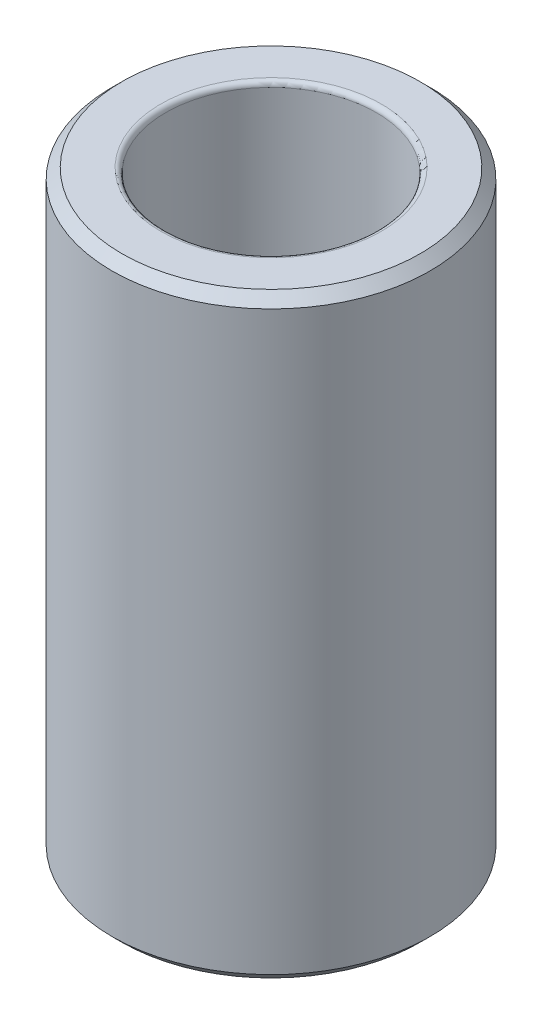
SolidWorks part; units mm, degrees
material "Stainless Steel (ferritic)"
ref_plane "Front Plane" through (0, 0, 0) normal (0, 0, 1) x (1, 0, 0)
ref_plane "Top Plane" through (0, 0, 0) normal (0, 1, 0) x (1, 0, 0)
ref_plane "Right Plane" through (0, 0, 0) normal (1, 0, 0) x (0, 0, -1)
sketch "Sketch2" plane through (0, 0, 0) normal (0, 1, 0) x (1, 0, 0)
  circle A0 centre (0, 0) radius 4
  circle A1 centre (0, 0) radius 2.65
  dimension "D1" = 8
  dimension "D2" = 5.3
extrude "Boss-Extrude1" add sketch "Sketch2" along normal blind 15
chamfer "Chamfer1" distance 0.25 angle 45 2 edges at (0, 0, 4) (0, 15, 4)
fillet "Fillet2" radius 0.125 2 edges at (0, 0, 2.65) (0, 15, 2.65)
